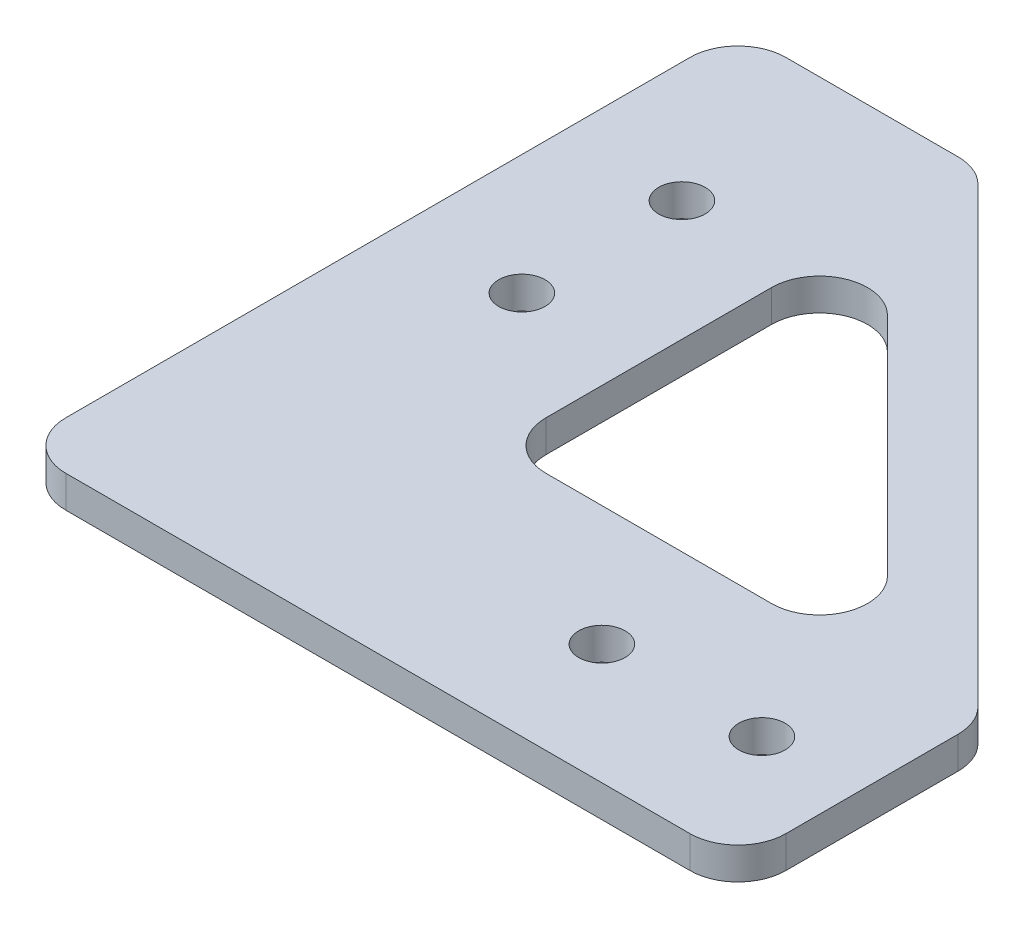
SolidWorks part; units mm, degrees
material "Thornel Mat VMA"
ref_plane "前视基准面" through (0, 0, 0) normal (0, 0, 1) x (1, 0, 0)
ref_plane "上视基准面" through (0, 0, 0) normal (0, 1, 0) x (1, 0, 0)
ref_plane "右视基准面" through (0, 0, 0) normal (1, 0, 0) x (0, 0, -1)
other "Configuration Table"
sketch "草图1" plane through (0, 0, 0) normal (0, 1, 0) x (1, 0, 0)
  line L0 (15, 45) -> (45, 15)
  line L1 (0, 0) -> (45, 0)
  line L2 (0, 0) -> (0, 15)
  line L3 (0, 15) -> (45, 15) construction
  line L4 (45, 0) -> (45, 15)
  line L5 (0, 0) -> (15, 0)
  line L6 (0, 0) -> (0, 45)
  line L7 (0, 45) -> (15, 45)
  line L8 (15, 0) -> (15, 45) construction
  line L9 (15, 39.3431) -> (15, 15)
  line L10 (15, 15) -> (39.3431, 15)
  line L11 (39.3431, 15) -> (15, 39.3431)
  line L12 (-7.1481, 7.5) -> (61.7407, 7.5) construction
  line L13 (7.5, 46.8519) -> (7.5, -6.4815) construction
  circle A0 centre (29, 7.5) radius 1.45
  circle A1 centre (39, 7.5) radius 1.45
  circle A2 centre (7.5, 24) radius 1.45
  circle A3 centre (7.5, 34) radius 1.45
  dimension "D6" = 9
  dimension "D7" = 10
  dimension "D9" = 10
  dimension "D10" = 2.9
  dimension "D1" = 15
  dimension "D2" = 15
  dimension "D3" = 45
  dimension "D4" = 45
  dimension "D5" = 4
  dimension "D8" = 14
extrude "凸台-拉伸1" add sketch "草图1" along normal blind 2 contours L7 L6 L2 L1 L4 L0 A3 A2 A1 A0 L11 L10 L9
fillet "圆角1" radius 3 8 edges at (45, 1, 0) (0, 1, 0) (0, 1, -45) (15, 1, -39.3431) (15, 1, -15) (39.3431, 1, -15) (15, 1, -45) (45, 1, -15)
